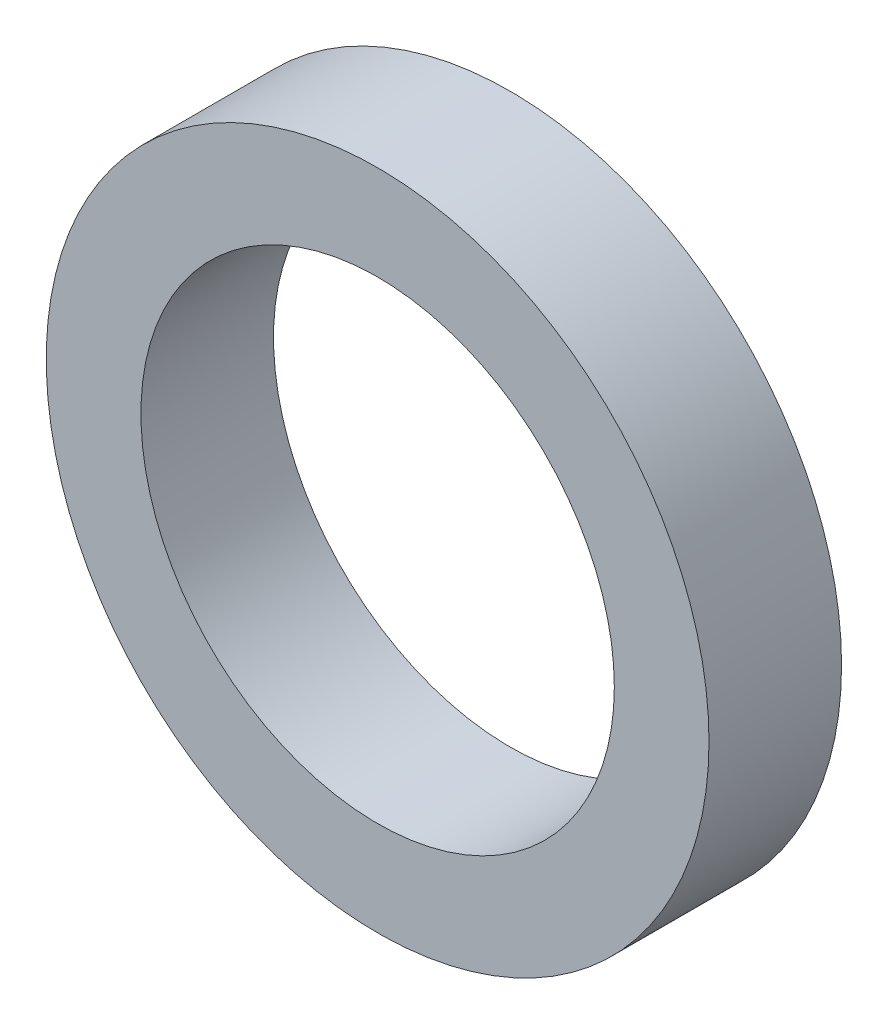
SolidWorks part; units mm, degrees
ref_plane "Front" through (0, 0, 0) normal (0, 0, 1) x (1, 0, 0)
ref_plane "Top" through (0, 0, 0) normal (0, 1, 0) x (1, 0, 0)
ref_plane "Right" through (0, 0, 0) normal (1, 0, 0) x (0, 0, -1)
sketch "Sketch1" plane through (0, 0, 0) normal (0, 0, 1) x (1, 0, 0)
  circle A0 centre (0, 0) radius 35
  circle A1 centre (0, 0) radius 25
  dimension "D1" = 70
  dimension "D2" = 50
extrude "Boss-Extrude1" add sketch "Sketch1" along normal blind 14
